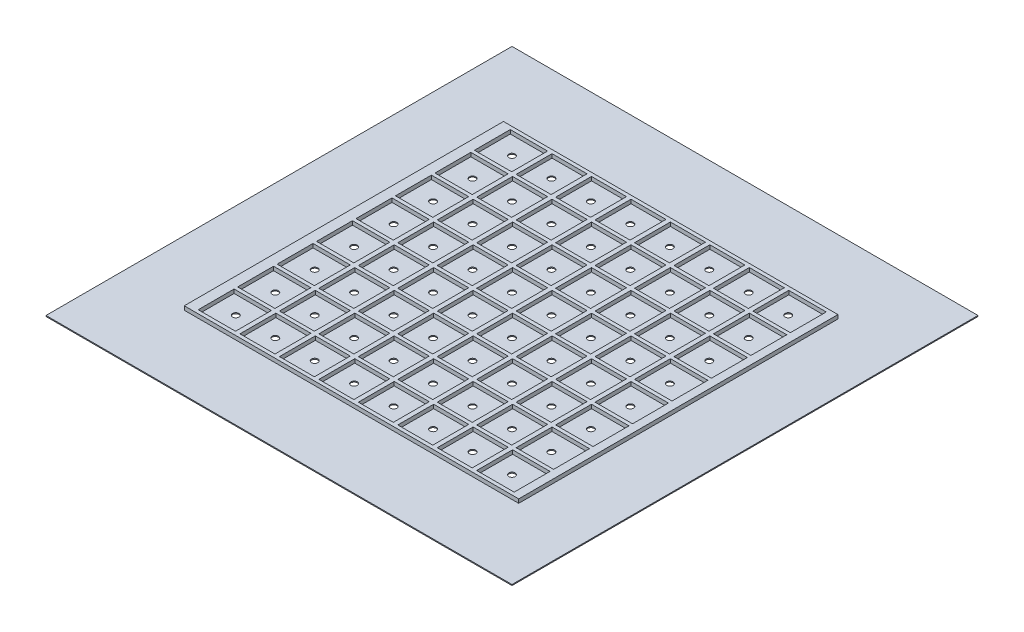
SolidWorks part; units mm, degrees
ref_plane "Front Plane" through (0, 0, 0) normal (0, 0, 1) x (1, 0, 0)
ref_plane "Top Plane" through (0, 0, 0) normal (0, 1, 0) x (1, 0, 0)
ref_plane "Right Plane" through (0, 0, 0) normal (1, 0, 0) x (0, 0, -1)
sketch "Sketch1" plane through (0, 0, 0) normal (0, 1, 0) x (1, 0, 0)
  line L1 (-300, -300) -> (300, -300)
  line L2 (-300, -300) -> (-300, 300)
  line L3 (-300, 300) -> (300, 300)
  line L4 (300, -300) -> (300, 300)
  line L5 (0, 300) -> (0, -300) construction
  line L6 (-300, 0) -> (300, 0) construction
  point P0 (0, 0)
extrude "Boss-Extrude1" add sketch "Sketch1" along normal blind 1.2426
sketch "Sketch2" plane through (0, 1.2426, 0) normal (0, 1, 0) x (1, 0, 0)
  line L1 (203.4, -203.4) -> (-203.4, -203.4)
  line L2 (203.4, -203.4) -> (203.4, 203.4)
  line L3 (203.4, 203.4) -> (-203.4, 203.4)
  line L4 (-203.4, -203.4) -> (-203.4, 203.4)
  line L5 (0, 203.4) -> (0, -203.4) construction
  line L6 (203.4, 0) -> (-203.4, 0) construction
  point P0 (0, 0)
sketch "Sketch3" plane through (0, 1.2426, 0) normal (0, 1, 0) x (1, 0, 0)
  line L1 (-203.4, 203.4) -> (-152.6, 203.4)
  line L2 (-203.4, 203.4) -> (-203.4, 152.6)
  line L3 (-203.4, 152.6) -> (-152.6, 152.6)
  line L4 (-152.6, 203.4) -> (-152.6, 152.6)
  point P5 (-178, 178)
  dimension "D1" = 50.8
  dimension "D2" = 50.8
sketch "Sketch6" plane through (0, 1.2426, 0) normal (0, 1, 0) x (1, 0, 0)
  circle A0 centre (-178, 178) radius 4.1
  dimension "D1" = 8.2
extrude "Cut-Extrude1" cut sketch "Sketch6" against normal through all
pattern_linear "LPattern1" count 8 spacing 50.8 along (1, 0, 0) count 8 spacing 50.8 along (0, 0, 1) of "Cut-Extrude1"
sketch "Sketch7" plane through (0, 1.2426, 0) normal (0, 1, 0) x (1, 0, 0)
  line L0 (-203.3894, 150.385) -> (-203.3894, 154.985)
  line L1 (-203.3894, 150.385) -> (203.4078, 150.385)
  line L2 (-203.3894, 154.985) -> (203.4078, 154.985)
  line L3 (203.4078, 150.385) -> (203.4078, 154.985)
extrude "Boss-Extrude4" add sketch "Sketch7" along normal blind 5
pattern_linear "LPattern3" count 8 spacing 50.8 along (0, 0, 1) count 2 spacing 50.8 along (0, 0, -1) of "Boss-Extrude4"
sketch "Sketch9" plane through (0, 1.2426, 0) normal (0, 1, 0) x (1, 0, 0)
  line L1 (-203.3894, 205.785) -> (-216.7491, 205.785)
  line L2 (-203.3894, 205.785) -> (-203.3894, -205.215)
  line L3 (-203.3894, -205.215) -> (-216.7491, -205.215)
  line L4 (-216.7491, 205.785) -> (-216.7491, -205.215)
  line L5 (203.4078, 205.785) -> (213.8412, 205.785)
  line L6 (203.4078, 205.785) -> (203.4078, -205.215)
  line L7 (203.4078, -205.215) -> (213.8412, -205.215)
  line L8 (213.8412, 205.785) -> (213.8412, -205.215)
extrude "Boss-Extrude5" add sketch "Sketch9" along normal blind 5
sketch "Sketch10" plane through (0, 1.2426, 0) normal (0, 1, 0) x (1, 0, 0)
  line L0 (-203.3894, 201.185) -> (203.4078, 201.185) construction
  line L1 (-155.4014, 201.185) -> (-149.6235, 201.185)
  line L2 (-155.4014, 201.185) -> (-155.4014, 154.985)
  line L3 (-155.4014, 154.985) -> (-149.6235, 154.985)
  line L4 (-149.6235, 201.185) -> (-149.6235, 154.985)
  line L5 (203.4078, 154.985) -> (-203.3894, 154.985) construction
extrude "Boss-Extrude6" add sketch "Sketch10" along normal blind 5
pattern_linear "LPattern4" count 7 spacing 50.8 along (1, 0, 0) count 8 spacing 50.8 along (0, 0, 1) of "Boss-Extrude6"
